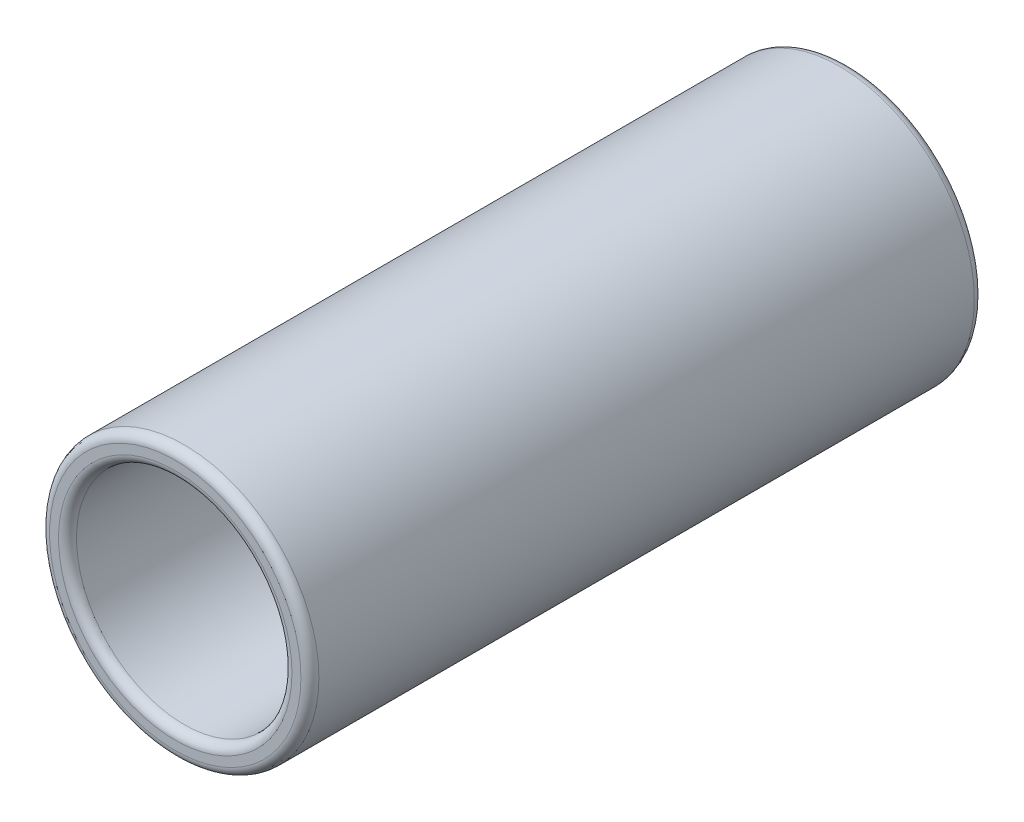
SolidWorks part; units mm, degrees
ref_plane "Ebene vorne" through (0, 0, 0) normal (0, 0, 1) x (1, 0, 0)
ref_plane "Ebene oben" through (0, 0, 0) normal (0, 1, 0) x (1, 0, 0)
ref_plane "Ebene rechts" through (0, 0, 0) normal (1, 0, 0) x (0, 0, -1)
sketch "Sketch1" plane through (0, 0, 0) normal (0, 0, 1) x (1, 0, 0)
  circle A0 centre (0, 0) radius 1.2
  circle A1 centre (0, 0) radius 1.5
  dimension "D1" = 2.4
  dimension "D2" = 3
extrude "Boss-Extrude1" add sketch "Sketch1" along normal blind 7.5
fillet "Fillet2" radius 0.1 4 edges at (1.2, 0, 0) (1.5, 0, 0) (1.5, 0, 7.5) (1.2, 0, 7.5)
